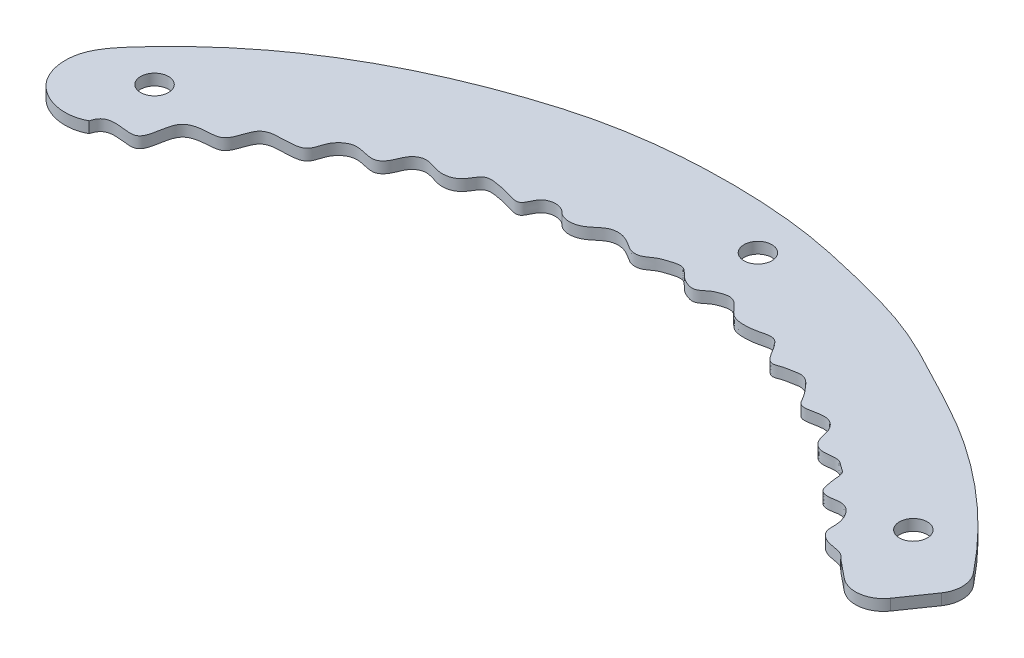
SolidWorks part; units mm, degrees
ref_plane "前视基准面" through (0, 0, 0) normal (0, 0, 1) x (1, 0, 0)
ref_plane "上视基准面" through (0, 0, 0) normal (0, 1, 0) x (1, 0, 0)
ref_plane "右视基准面" through (0, 0, 0) normal (1, 0, 0) x (0, 0, -1)
sketch "草图1" plane through (0, 0, 0) normal (0, 1, 0) x (1, 0, 0)
  line L0 (1.5548, -8.3375) -> (-0.4302, -6.7213)
  line L1 (8.1432, -4.501) -> (5.9156, -7.7187)
  circle A0 centre (-81.4137, 0.5413) radius 1.5
  circle A1 centre (0.783, -0.1362) radius 1.5
  circle A2 centre (-33.3548, 17.3022) radius 1.5
  arc A3 (1.5548, -8.3375) -> (5.9156, -7.7187) centre (3.449, -6.0111) ccw
  arc A4 (8.0213, -0.9218) -> (-4.5749, 10.6629) centre (-35.7028, -35.823) ccw
  arc A5 (8.1432, -4.501) -> (8.0213, -0.9218) centre (5.6767, -2.7934) ccw
  spline S0 degree 3 poles (-12.167, 2.5825) (-11.4471, 1.9213) (-10.023, 2.8082) (-8.9764, 1.8091) (-8.2135, 1.404) (-8.2004, 0.3499) (-8.0426, -0.494) (-7.819, -1.4294) (-6.8169, -1.7535) (-5.8636, -1.3425) (-4.7413, -1.711) (-4.0828, -2.6214) (-3.7925, -3.7512) (-3.9105, -4.8693) (-3.2321, -5.6268) (-2.2067, -6.0304) (-1.0461, -6.0626) (-0.5549, -6.5645) (-0.4302, -6.7213) knots 0 0 0 0 0.036098 0.047993 0.058182 0.069735 0.087709 0.096698 0.107024 0.126401 0.138603 0.153227 0.171393 0.187122 0.197486 0.211172 0.233173 0.241578 0.241578 0.241578 0.241578
  spline S1 degree 3 poles (-23.9106, 9.6057) (-23.5583, 9.383) (-22.85, 7.3001) (-21.4691, 8.0266) (-20.5876, 8.1152) (-19.7095, 8.3931) (-18.8874, 8.017) (-18.2164, 7.2706) (-17.5409, 6.4954) (-16.9173, 5.1698) (-15.3663, 5.5887) (-13.9067, 5.7479) (-12.701, 4.3501) (-12.8698, 3.1094) (-12.167, 2.5825) knots 0 0 0 0 0.161236 0.212348 0.265446 0.336193 0.378688 0.430637 0.526782 0.58317 0.682557 0.781271 0.853714 1 1 1 1
  spline S2 degree 3 poles (-47.715, 10.6051) (-47.069, 9.9007) (-45.1392, 9.958) (-43.922, 11.5864) (-42.4007, 11.771) (-41.3375, 11.3077) (-40.4081, 10.5714) (-39.2433, 10.6059) (-38.4214, 11.3898) (-37.3041, 11.739) (-35.96, 12.1777) (-35.1697, 11.0959) (-34.3091, 10.5976) (-33.2302, 10.3268) (-32.4836, 11.1725) (-31.5559, 11.5569) (-30.4962, 11.8332) (-29.5446, 11.0114) (-28.7649, 9.931) (-27.275, 9.7916) (-25.6779, 9.9955) (-24.4296, 10.4937) (-23.9106, 9.6057) knots 0 0 0 0 0.101433 0.182304 0.213922 0.268057 0.309966 0.345938 0.38914 0.432999 0.482664 0.529097 0.56672 0.598853 0.644173 0.680167 0.715861 0.759457 0.810996 0.863338 0.916048 1 1 1 1
  spline S3 degree 3 poles (-81.5422, -6.3513) (-81.0448, -4.2136) (-76.4233, -7.0442) (-77.1939, -1.4346) (-74.4996, -1.0071) (-72.1196, -0.982) (-72.0139, 2.5319) (-69.1934, 2.2708) (-66.979, 2.5768) (-66.7933, 4.5615) (-65.2282, 5.8665) (-63.7043, 5.4312) (-62.4807, 5.2334) (-61.4837, 6.1991) (-61.3006, 7.5032) (-59.7831, 8.3976) (-58.5198, 7.7031) (-57.096, 7.6588) (-55.836, 8.2946) (-55.3246, 9.9013) (-53.5853, 9.7021) (-52.4002, 9.4229) (-50.5844, 8.8131) (-50.168, 11.1139) (-48.3352, 11.1661) (-47.715, 10.6051) knots 0 0 0 0 0.100332 0.18604 0.234954 0.2703 0.337742 0.40192 0.43828 0.47683 0.523229 0.559517 0.584173 0.604077 0.648703 0.670042 0.71595 0.738313 0.768611 0.808998 0.834826 0.875875 0.9064 0.941714 1 1 1 1
  spline S4 degree 3 poles (-4.5749, 10.6629) (-7.0478, 12.3188) (-11.4724, 14.6182) (-18.6446, 18.4463) (-25.5528, 20.2853) (-32.3111, 21.7651) (-38.4562, 22.3345) (-46.0367, 22.338) (-53.5806, 21.3214) (-60.3919, 19.2596) (-67.9165, 16.4006) (-77.0441, 11.4902) (-84.2299, 5.0961) (-88.4718, 0.1048) (-88.5463, -3.0993) (-86.896, -6.5347) (-83.4963, -7.4095) (-81.5422, -6.3513) knots 0.083499 0.083499 0.083499 0.083499 0.162309 0.214041 0.297346 0.349154 0.396315 0.45953 0.548645 0.595484 0.646703 0.76082 0.864659 0.902713 0.926128 0.944547 1 1 1 1
extrude "凸台-拉伸1" add sketch "草图1" along normal blind 1.2
